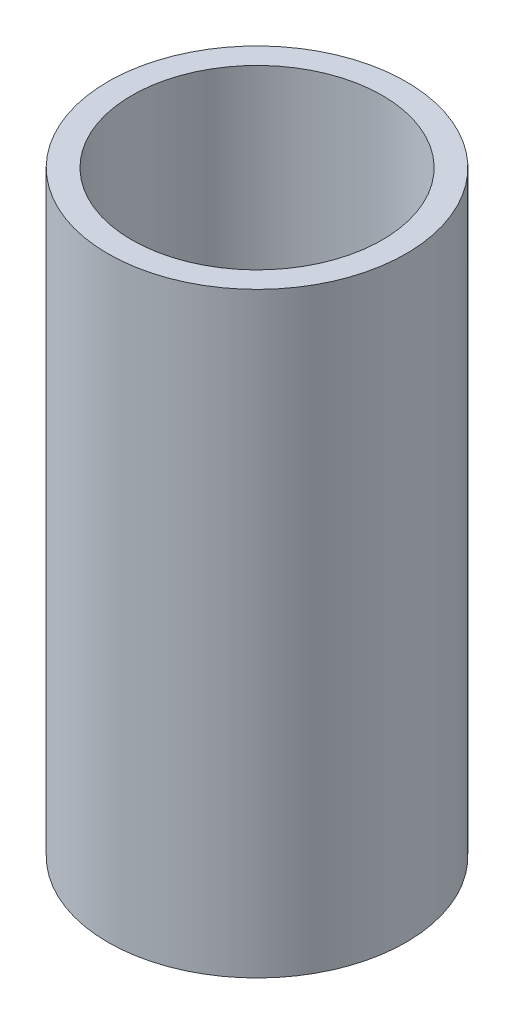
SolidWorks part; units mm, degrees
ref_plane "Front Plane" through (0, 0, 0) normal (0, 0, 1) x (1, 0, 0)
ref_plane "Top Plane" through (0, 0, 0) normal (0, 1, 0) x (1, 0, 0)
ref_plane "Right Plane" through (0, 0, 0) normal (1, 0, 0) x (0, 0, -1)
sketch "Sketch1" plane through (0, 0, 0) normal (0, 1, 0) x (1, 0, 0)
  circle A0 centre (0, 0) radius 12.5
  circle A1 centre (0, 0) radius 10.5
  dimension "D1" = 21
  dimension "D2" = 25
extrude "Boss-Extrude1" add sketch "Sketch1" along normal mid plane 50
